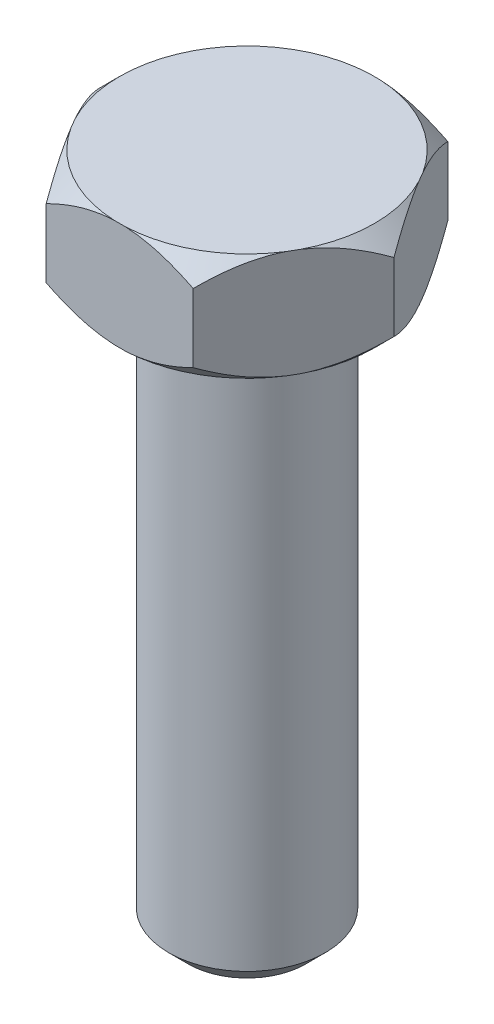
SolidWorks part; units mm, degrees
ref_plane "Спереди" through (0, 0, 0) normal (0, 0, 1) x (1, 0, 0)
ref_plane "Сверху" through (0, 0, 0) normal (0, 1, 0) x (1, 0, 0)
ref_plane "Справа" through (0, 0, 0) normal (1, 0, 0) x (0, 0, -1)
sketch "Эскиз1" plane through (0, 0, 0) normal (0, 1, 0) x (1, 0, 0)
  line L0 (-3.7528, 6.5) -> (3.7528, 6.5)
  line L1 (3.7528, 6.5) -> (7.5056, 0)
  line L2 (7.5056, 0) -> (3.7528, -6.5)
  line L3 (3.7528, -6.5) -> (-3.7528, -6.5)
  line L4 (-3.7528, -6.5) -> (-7.5056, 0)
  line L5 (-7.5056, 0) -> (-3.7528, 6.5)
  dimension "D5" = 6.5
  dimension "D2" = 120
  dimension "D3" = 120
  dimension "D4" = 120
  dimension "D6" = 6.5
  dimension "D7" = 6.5
  dimension "D8" = 6.5
  dimension "D9" = 6.5
  dimension "D10" = 120
  dimension "D11" = 6.5
extrude "Вытянуть1" add sketch "Эскиз1" against normal blind 5.5
sketch "Эскиз5" plane through (0, -5.5, 0) normal (0, -1, 0) x (1, 0, 0)
  circle A0 centre (0, 0) radius 4
  dimension "D1" = 8
extrude "Вытянуть2" add sketch "Эскиз5" along normal blind 29
chamfer "Фаска1" distance 1 angle 45 1 edges at (0, -34.5, -4)
ref_axis "Ось1" through (0, -5.5, 0) along (0, -1, 0)
ref_plane "Плоскость1" through (0, 0, 0) normal (0, 0, 1) x (1, 0, 0)
sketch "Эскиз4" plane through (0, 0, 0) normal (0, 0, 1) x (1, 0, 0)
  line L0 (-7.5056, -1) -> (-6.5056, 0)
  line L1 (-7.5056, -5.5) -> (-7.5056, 0) construction
  line L2 (-7.5056, 0) -> (-3.7528, 0) construction
  line L3 (-6.5056, 0) -> (-7.5056, 0)
  line L4 (-7.5056, 0) -> (-7.5056, -1)
  line L5 (-7.5056, -4.5) -> (-6.5056, -5.5)
  line L6 (-7.5056, -5.5) -> (-3.7528, -5.5) construction
  line L7 (-6.5056, -5.5) -> (-7.5056, -5.5)
  line L8 (-7.5056, -5.5) -> (-7.5056, -4.5)
  dimension "D1" = 1
  dimension "D2" = 1
  dimension "D3" = 1
  dimension "D4" = 1
revolve "Вырез-Повернуть1" cut sketch "Эскиз4" angle 360 about axis through (0, -5.5, 0) along (0, -1, 0)
